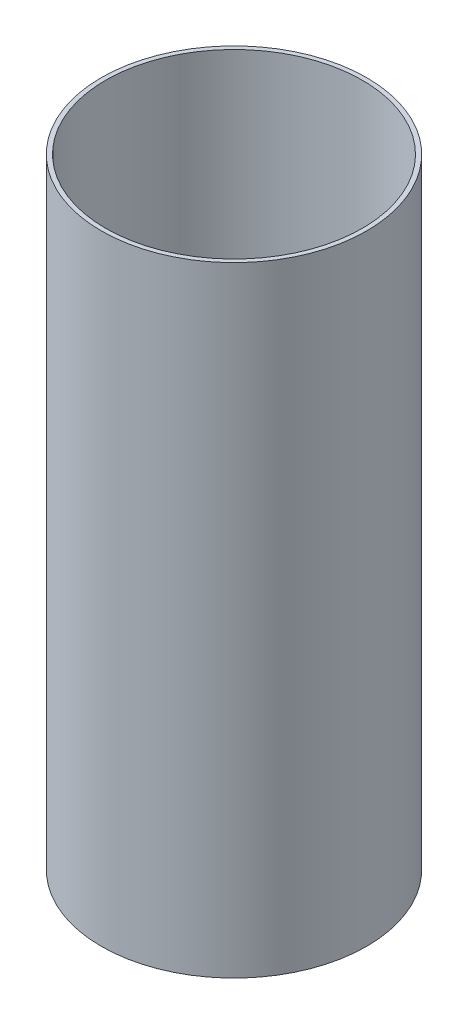
SolidWorks part; units mm, degrees
ref_plane "Front Plane" through (0, 0, 0) normal (0, 0, 1) x (1, 0, 0)
ref_plane "Top Plane" through (0, 0, 0) normal (0, 1, 0) x (1, 0, 0)
ref_plane "Right Plane" through (0, 0, 0) normal (1, 0, 0) x (0, 0, -1)
sketch "Sketch1" plane through (0, 0, 0) normal (0, 1, 0) x (1, 0, 0)
  circle A0 centre (0, 0) radius 76.1746
  circle A1 centre (0, 0) radius 73.66
  dimension "D1" = 152.3492
  dimension "D2" = 147.32
extrude "Boss-Extrude1" add sketch "Sketch1" along normal blind 355.6
equation "\"Mid_Coupler_Length\" = 14in"
equation "\"D1@Boss-Extrude1\"=\"Mid_Coupler_Length\""
